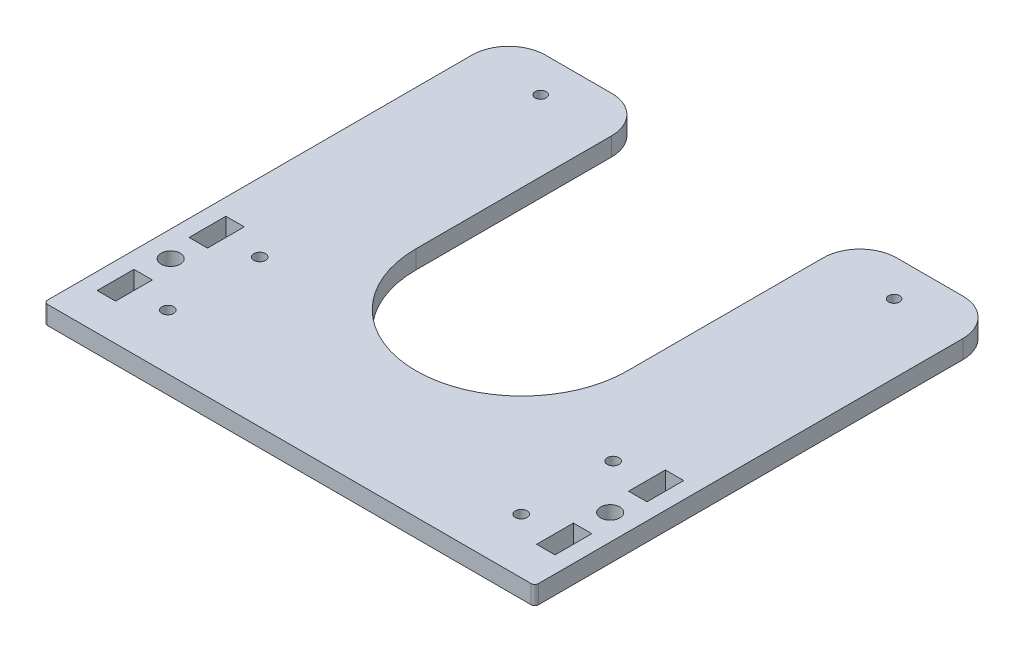
SolidWorks part; units mm, degrees
material "6061 Alloy"
ref_plane "Front Plane" through (0, 0, 0) normal (0, 0, 1) x (1, 0, 0)
ref_plane "Top Plane" through (0, 0, 0) normal (0, 1, 0) x (1, 0, 0)
ref_plane "Right Plane" through (0, 0, 0) normal (1, 0, 0) x (0, 0, -1)
sketch "Sketch1" plane through (0, 0, 0) normal (0, 1, 0) x (1, 0, 0)
  line L0 (-66.75, 63.2) -> (66.75, 63.2)
  line L1 (66.75, 63.2) -> (66.75, -63.2)
  line L2 (-66.75, -63.2) -> (66.75, -63.2)
  line L3 (-66.75, 63.2) -> (-66.75, -63.2)
  line L4 (-52.75, -49.2) -> (-66.75, -49.2) construction
  line L5 (-59.75, -53.2) -> (-59.75, -18.2) construction
  line L6 (0, 49.2) -> (0, -49.2) construction
  line L7 (-62.25, -43.2) -> (-57.25, -43.2)
  line L8 (-62.25, -43.2) -> (-62.25, -53.2)
  line L9 (-62.25, -53.2) -> (-57.25, -53.2)
  line L10 (-57.25, -43.2) -> (-57.25, -53.2)
  line L11 (-52.75, 49.2) -> (52.75, 49.2) construction
  line L12 (-52.75, 49.2) -> (-52.75, -49.2) construction
  line L13 (-52.75, -49.2) -> (52.75, -49.2) construction
  line L14 (52.75, 49.2) -> (52.75, -49.2) construction
  line L15 (-52.75, 49.2) -> (52.75, -49.2) construction
  line L16 (-52.75, -49.2) -> (52.75, 49.2) construction
  line L17 (-62.25, -28.2) -> (-57.25, -28.2)
  line L18 (-62.25, -28.2) -> (-62.25, -18.2)
  line L19 (-62.25, -18.2) -> (-57.25, -18.2)
  line L20 (-57.25, -28.2) -> (-57.25, -18.2)
  line L21 (62.25, -18.2) -> (57.25, -18.2)
  line L22 (57.25, -28.2) -> (57.25, -18.2)
  line L23 (62.25, -28.2) -> (62.25, -18.2)
  line L24 (62.25, -28.2) -> (57.25, -28.2)
  line L25 (57.25, -43.2) -> (57.25, -53.2)
  line L26 (62.25, -43.2) -> (57.25, -43.2)
  line L27 (62.25, -43.2) -> (62.25, -53.2)
  line L28 (62.25, -53.2) -> (57.25, -53.2)
  circle A0 centre (-59.75, -35.7) radius 2.6
  circle A1 centre (59.75, -35.7) radius 2.6
  circle A2 centre (-48.05, -48.2) radius 1.6
  circle A3 centre (48.05, -48.2) radius 1.6
  point P0 (0, 0)
  point P10 (0, 0)
  point P36 (-59.75, -49.2)
  dimension "D8" = 5.2
  dimension "D9" = 3.2
  dimension "D1" = 98.4
  dimension "D2" = 14
  dimension "D3" = 5
  dimension "D4" = 10
  dimension "D5" = 105.5
  dimension "D6" = 10
  dimension "D7" = 35
extrude "Boss-Extrude1" add sketch "Sketch1" along normal blind 5
sketch "Sketch2" plane through (0, 5, 0) normal (0, 1, 0) x (1, 0, 0)
  line L0 (-28.75, 86.6787) -> (-28.75, 0)
  line L1 (-28.75, 86.6787) -> (28.75, 86.6787)
  line L2 (66.75, 63.2) -> (-66.75, 63.2) construction
  line L3 (0, 63.2) -> (0, 0) construction
  line L4 (28.75, 86.6787) -> (28.75, 0)
  arc A0 (-28.75, 0) -> (28.75, 0) centre (0, 0) ccw
  point P10 (0, 86.6787)
  dimension "D1" = 28.75
extrude "Cut-Extrude2" cut sketch "Sketch2" against normal blind 10 contours L0 A0 L4 L1
fillet "Fillet2" radius 10 4 edges at (66.75, 2.5, -63.2) (28.75, 2.5, -63.2) (-66.75, 2.5, -63.2) (-28.75, 2.5, -63.2)
sketch "Sketch5" plane through (0, 0, 0) normal (0, -1, 0) x (1, 0, 0)
  line L0 (0, 0) -> (0, 58.2) construction
  line L1 (-65.75, 58.2) -> (65.75, 58.2) construction
  circle A0 centre (48.05, 23.2) radius 1.6
  circle A2 centre (48.05, -53.2) radius 1.5
  circle A3 centre (48.05, -53.2) radius 1.5 construction
  circle A4 centre (-48.05, -53.2) radius 1.5
  circle A5 centre (-48.05, 23.2) radius 1.6
  dimension "D1" = 3.2
extrude "Cut-Extrude3" cut sketch "Sketch5" against normal up to next
fillet "Fillet3" radius 1 2 edges at (-66.75, 2.5, 63.2) (66.75, 2.5, 63.2)
